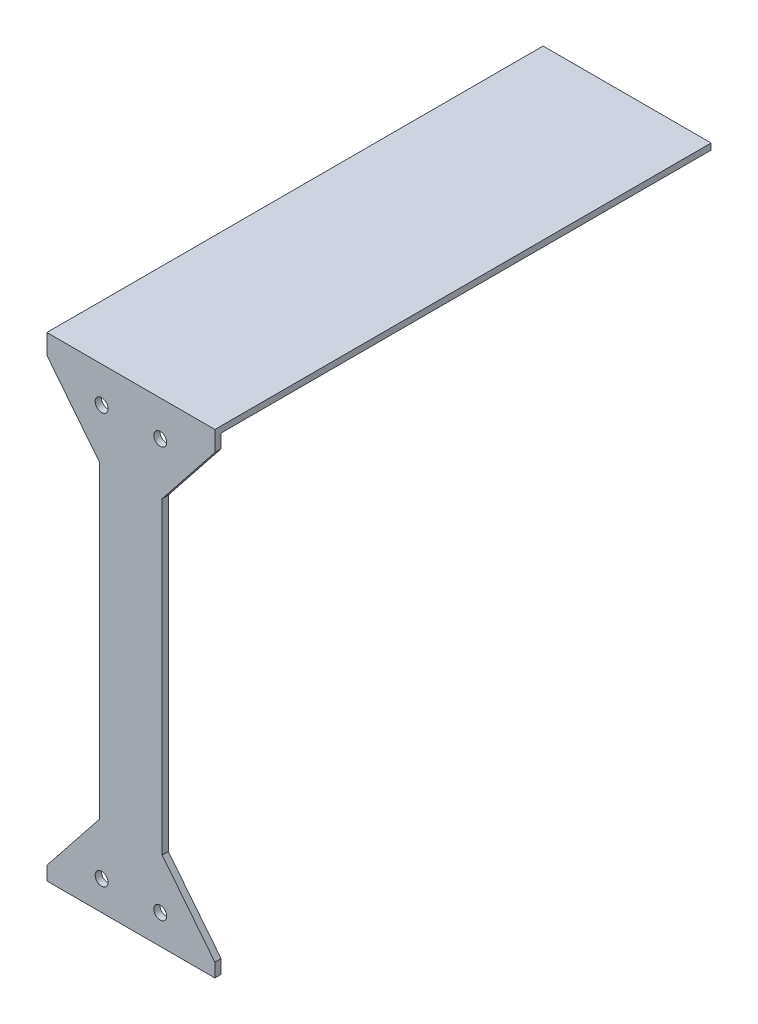
SolidWorks part; units mm, degrees
ref_plane "Front Plane" through (0, 0, 0) normal (0, 0, 1) x (1, 0, 0)
ref_plane "Top Plane" through (0, 0, 0) normal (0, 1, 0) x (1, 0, 0)
ref_plane "Right Plane" through (0, 0, 0) normal (1, 0, 0) x (0, 0, -1)
sketch "Sketch1" plane through (0, 0, 0) normal (0, 0, 1) x (1, 0, 0)
  line L0 (-117, 99.5) -> (-103.5, 116.5) construction
  line L1 (-146.5, 116.5) -> (-133, 99.5) construction
  line L2 (-133, 99.5) -> (-117, 99.5) construction
  line L3 (-117, 99.5) -> (-103.5, 116.5)
  line L4 (-146.5, 116.5) -> (-133, 99.5)
  line L5 (-133, 99.5) -> (-117, 99.5) construction
  line L6 (-250, 120) -> (0, 120) construction
  line L7 (-146.5, 120) -> (-103.5, 120)
  line L8 (0, 0) -> (-250, 0) construction
  line L9 (-103.5, 3.5) -> (-117, 20.5) construction
  line L10 (-117, 20.5) -> (-133, 20.5) construction
  line L11 (-133, 20.5) -> (-146.5, 3.5) construction
  line L12 (-103.5, 0) -> (-146.5, 0)
  line L13 (-103.5, 3.5) -> (-117, 20.5)
  line L14 (-117, 20.5) -> (-133, 20.5) construction
  line L15 (-133, 20.5) -> (-146.5, 3.5)
  line L16 (-103.5, 3.5) -> (-103.5, 0)
  line L18 (-146.5, 3.5) -> (-146.5, 0)
  line L19 (-103.5, 116.5) -> (-103.5, 120)
  line L20 (-146.5, 116.5) -> (-146.5, 120)
  line L21 (-117, 20.5) -> (-117, 99.5)
  line L22 (-133, 99.5) -> (-133, 20.5)
  arc A0 (-134.15, 112.5) -> (-130.85, 112.5) centre (-132.5, 112.5) ccw construction
  arc A1 (-130.85, 112.5) -> (-134.15, 112.5) centre (-132.5, 112.5) ccw construction
  arc A2 (-119.15, 112.5) -> (-115.85, 112.5) centre (-117.5, 112.5) ccw construction
  arc A3 (-115.85, 112.5) -> (-119.15, 112.5) centre (-117.5, 112.5) ccw construction
  arc A4 (-134.15, 112.5) -> (-130.85, 112.5) centre (-132.5, 112.5) ccw
  arc A5 (-130.85, 112.5) -> (-134.15, 112.5) centre (-132.5, 112.5) ccw
  arc A6 (-119.15, 112.5) -> (-115.85, 112.5) centre (-117.5, 112.5) ccw
  arc A7 (-115.85, 112.5) -> (-119.15, 112.5) centre (-117.5, 112.5) ccw
  arc A8 (-115.85, 7.5) -> (-119.15, 7.5) centre (-117.5, 7.5) ccw construction
  arc A9 (-119.15, 7.5) -> (-115.85, 7.5) centre (-117.5, 7.5) ccw construction
  arc A10 (-134.15, 7.5) -> (-130.85, 7.5) centre (-132.5, 7.5) ccw construction
  arc A11 (-130.85, 7.5) -> (-134.15, 7.5) centre (-132.5, 7.5) ccw construction
  arc A12 (-115.85, 7.5) -> (-119.15, 7.5) centre (-117.5, 7.5) ccw
  arc A13 (-119.15, 7.5) -> (-115.85, 7.5) centre (-117.5, 7.5) ccw
  arc A14 (-134.15, 7.5) -> (-130.85, 7.5) centre (-132.5, 7.5) ccw
  arc A15 (-130.85, 7.5) -> (-134.15, 7.5) centre (-132.5, 7.5) ccw
extrude "Boss-Extrude1" add sketch "Sketch1" along normal blind 1.5875
sketch "Sketch2" plane through (0, 120, 0) normal (0, 1, 0) x (1, 0, 0)
  line L0 (-103.5, -1.5875) -> (-103.5, 125.4125)
  line L1 (-103.5, 125.4125) -> (-146.5, 125.4125)
  line L2 (-146.5, 125.4125) -> (-146.5, -1.5875)
  line L4 (-146.5, -1.5875) -> (-103.5, -1.5875)
  point P3 (-103.5, -1.5875)
  point P6 (0, 0)
  point P7 (0, 0)
  point P8 (-106.3602, -1.5875)
  point P9 (0, 0)
  point P13 (-103.5525, -1.5875)
  dimension "D1" = 127
extrude "Boss-Extrude2" add sketch "Sketch2" along normal blind 1.5875
